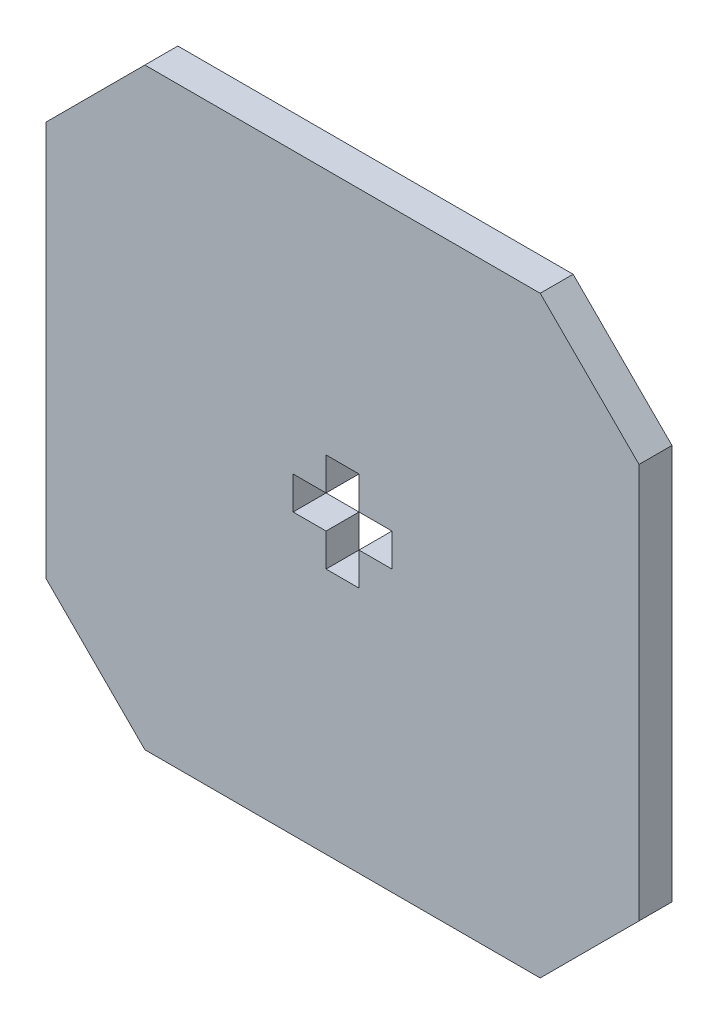
SolidWorks part; units mm, degrees
ref_plane "Front Plane" through (0, 0, 0) normal (0, 0, 1) x (1, 0, 0)
ref_plane "Top Plane" through (0, 0, 0) normal (0, 1, 0) x (1, 0, 0)
ref_plane "Right Plane" through (0, 0, 0) normal (1, 0, 0) x (0, 0, -1)
sketch "Sketch1" plane through (0, 0, 0) normal (0, 0, 1) x (1, 0, 0)
  line L1145 (307.5, 274.5) -> (307.5, 271.5)
  line L1146 (307.5, 271.5) -> (304.5, 271.5)
  line L1147 (304.5, 271.5) -> (304.5, 268.5)
  line L1148 (304.5, 268.5) -> (307.5, 268.5)
  line L1149 (307.5, 268.5) -> (307.5, 265.5)
  line L1150 (307.5, 265.5) -> (310.5, 265.5)
  line L1151 (310.5, 265.5) -> (310.5, 268.5)
  line L1152 (310.5, 268.5) -> (313.5, 268.5)
  line L1153 (313.5, 268.5) -> (313.5, 271.5)
  line L1154 (313.5, 271.5) -> (310.5, 271.5)
  line L1155 (310.5, 271.5) -> (310.5, 274.5)
  line L1156 (310.5, 274.5) -> (307.5, 274.5)
  line L1157 (336, 252) -> (327, 243)
  line L1158 (327, 243) -> (291, 243)
  line L1159 (291, 243) -> (282, 252)
  line L1160 (282, 252) -> (282, 288)
  line L1161 (282, 288) -> (291, 297)
  line L1162 (291, 297) -> (327, 297)
  line L1163 (327, 297) -> (336, 288)
  line L1164 (336, 288) -> (336, 252)
extrude "Boss-Extrude1" add sketch "Sketch1" along normal blind 3
